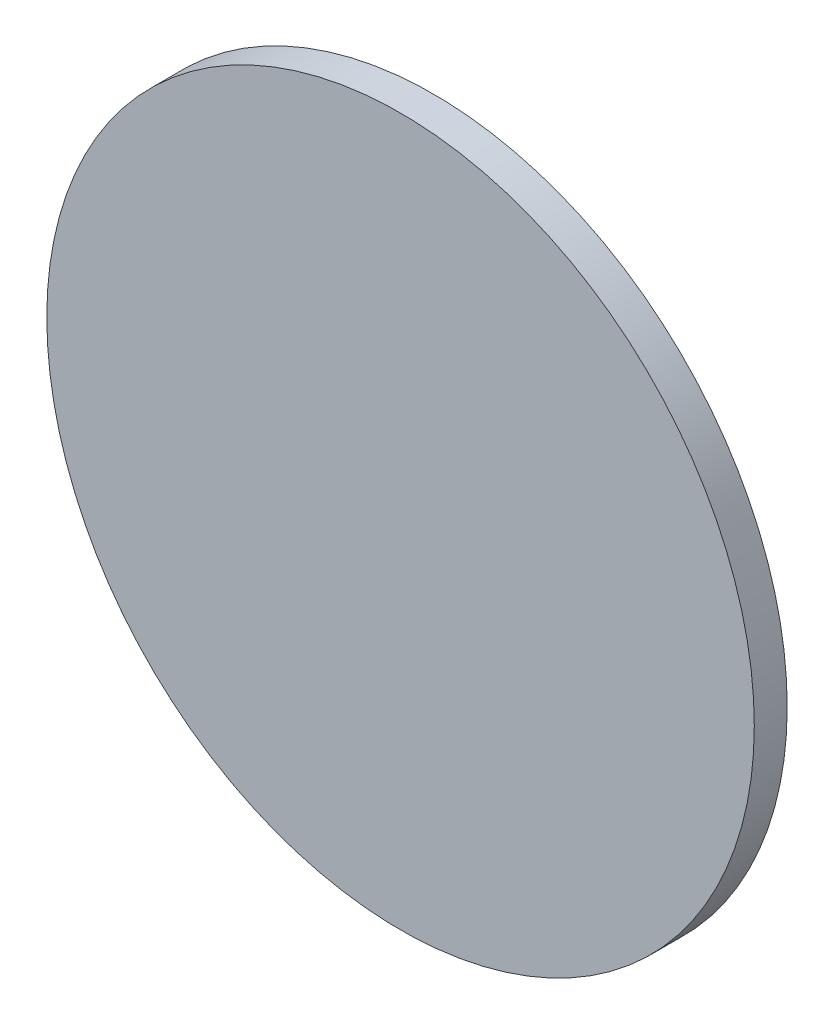
SolidWorks part; units mm, degrees
material "Acrylic (Medium-high impact)"
ref_plane "Front Plane" through (0, 0, 0) normal (0, 0, 1) x (1, 0, 0)
ref_plane "Top Plane" through (0, 0, 0) normal (0, 1, 0) x (1, 0, 0)
ref_plane "Right Plane" through (0, 0, 0) normal (1, 0, 0) x (0, 0, -1)
sketch "Sketch2" plane through (0, 0, 0) normal (0, 0, 1) x (1, 0, 0)
  circle A0 centre (0, 0) radius 32.25
  dimension "D1" = 64.5
extrude "Boss-Extrude1" add sketch "Sketch2" along normal blind 3
